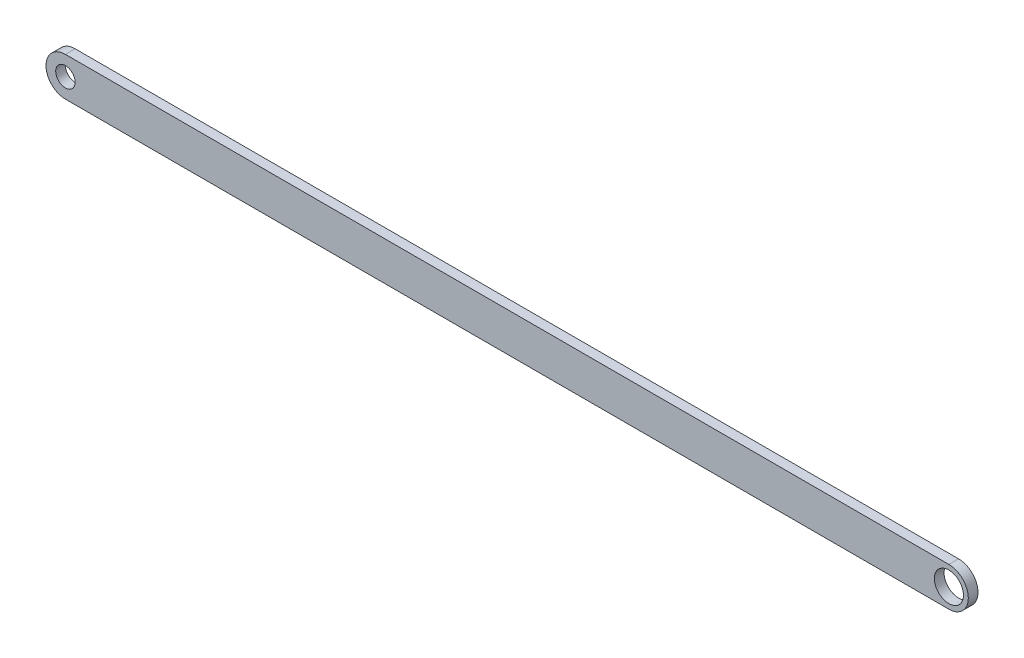
SolidWorks part; units mm, degrees
ref_plane "Plano frontal" through (0, 0, 0) normal (0, 0, 1) x (1, 0, 0)
ref_plane "Plano superior" through (0, 0, 0) normal (0, 1, 0) x (1, 0, 0)
ref_plane "Plano direito" through (0, 0, 0) normal (1, 0, 0) x (0, 0, -1)
sketch "Esboço1" plane through (0, 0, 0) normal (0, 0, 1) x (1, 0, 0)
  line L0 (-45.545, 2) -> (45.545, 2)
  line L1 (-14.0833, 0) -> (14.0833, 0) construction
  line L2 (-45.545, -2) -> (45.545, -2)
  arc A0 (-45.545, 2) -> (-45.545, -2) centre (-45.545, 0) ccw
  arc A1 (45.545, 2) -> (45.545, -2) centre (45.545, 0) cw
  circle A2 centre (45.545, 0) radius 1.5
  circle A3 centre (-45.545, 0) radius 1
  point P3 (0, 2)
  dimension "D3" = 3
  dimension "D1" = 2
  dimension "D2" = 91.09
extrude "Ressalto-extrusão1" add sketch "Esboço1" along normal blind 1
